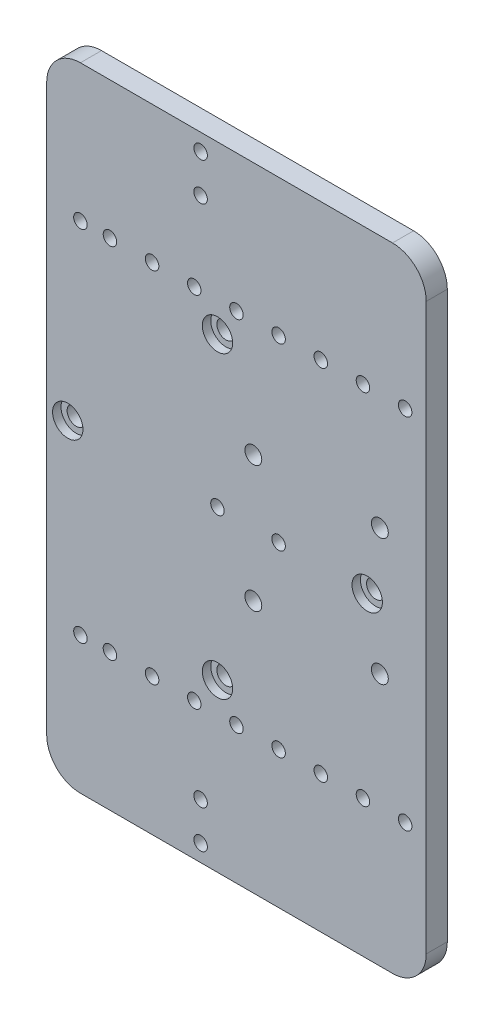
SolidWorks part; units mm, degrees
ref_plane "前视基准面" through (0, 0, 0) normal (0, 0, 1) x (1, 0, 0)
ref_plane "上视基准面" through (0, 0, 0) normal (0, 1, 0) x (1, 0, 0)
ref_plane "右视基准面" through (0, 0, 0) normal (1, 0, 0) x (0, 0, -1)
sketch "草图1" plane through (0, 0, 0) normal (0, 0, 1) x (1, 0, 0)
  line L1 (0, 0) -> (90, 0)
  line L2 (0, 0) -> (0, -150)
  line L3 (0, -150) -> (90, -150)
  line L4 (90, 0) -> (90, -150)
  circle A4 centre (79, -60) radius 2
  circle A5 centre (79, -90) radius 2
  circle A12 centre (49, -60) radius 2
  circle A13 centre (49, -90) radius 2
  circle A14 centre (40.5, -39.5) radius 2.15
  circle A15 centre (40.5, -110.5) radius 2.15
  circle A16 centre (76, -75) radius 2.15
  circle A17 centre (5, -75) radius 2.15
  circle A18 centre (85, -117.5) radius 1.6
  circle A19 centre (75, -117.5) radius 1.6
  circle A20 centre (65, -117.5) radius 1.6
  circle A21 centre (55, -117.5) radius 1.6
  circle A22 centre (45, -117.5) radius 1.6
  circle A23 centre (85, -32.5) radius 1.6
  circle A24 centre (75, -32.5) radius 1.6
  circle A25 centre (65, -32.5) radius 1.6
  circle A26 centre (55, -32.5) radius 1.6
  circle A27 centre (45, -32.5) radius 1.6
  circle A28 centre (35, -117.5) radius 1.6
  circle A29 centre (25, -117.5) radius 1.6
  circle A30 centre (15, -117.5) radius 1.6
  circle A31 centre (35, -32.5) radius 1.6
  circle A32 centre (25, -32.5) radius 1.6
  circle A33 centre (15, -32.5) radius 1.6
  circle A34 centre (8, -117.5) radius 1.6
  circle A35 centre (8, -32.5) radius 1.6
  circle A36 centre (36.5, -4) radius 1.6
  circle A37 centre (36.5, -13) radius 1.6
  circle A38 centre (36.5, -137) radius 1.6
  circle A39 centre (36.5, -146) radius 1.6
  circle A40 centre (55, -75) radius 1.6
  circle A41 centre (40.5, -75) radius 1.6
  dimension "D1" = 150
  dimension "D15" = 2
  dimension "D5" = 30
  dimension "D16" = 2
  dimension "D17" = 2
  dimension "D18" = 39.5
  dimension "D7" = 49
  dimension "D19" = 71
  dimension "D21" = 71
  dimension "D3" = 75
  dimension "D4" = 32.5
  dimension "D6" = 3.2
  dimension "D12" = 5
  dimension "D23" = 7
  dimension "D24" = 4
  dimension "D25" = 36.5
  dimension "D28" = 4
  dimension "D29" = 9
  dimension "D30" = 50
  dimension "D31" = 35.5
  dimension "D2" = 90
  dimension "D8" = 60
  dimension "D9" = 5
  dimension "D10" = 30
  dimension "D11" = 2
  dimension "D13" = 4
  dimension "D14" = 2
  dimension "D20" = 40.5
  dimension "D22" = 5
  dimension "D26" = 2
  dimension "D27" = 2
extrude "凸台-拉伸1" add sketch "草图1" along normal blind 5
fillet "圆角1" radius 8 4 edges at (0, -150, 2.5) (90, -150, 2.5) (90, 0, 2.5) (0, 0, 2.5)
sketch "草图2" plane through (0, 0, 5) normal (0, 0, 1) x (1, 0, 0)
  circle A0 centre (40.5, -39.5) radius 3.6
  circle A1 centre (76, -75) radius 3.6
  circle A2 centre (5, -75) radius 3.6
  circle A3 centre (40.5, -110.5) radius 3.6
  circle A5 centre (40.5, -39.5) radius 2.15 construction
  circle A6 centre (76, -75) radius 2.15 construction
  circle A7 centre (40.5, -110.5) radius 2.15 construction
  circle A8 centre (5, -75) radius 2.15 construction
extrude "切除-拉伸1" cut sketch "草图2" against normal blind 2
sketch "草图4" plane through (0, 0, 0) normal (0, 0, -1) x (-1, 0, 0)
  arc A0 (-42.1996, -35.0361) -> (-80.4639, -73.3004) centre (-40.5, -75) ccw
  arc A3 (-38.8004, -114.9639) -> (-42.1996, -114.9639) centre (-40.5, -110.5) ccw
  arc A4 (-80.4639, -76.6996) -> (-80.4639, -73.3004) centre (-76, -75) ccw
  arc A6 (-0.5361, -73.3004) -> (-0.5361, -76.6996) centre (-5, -75) ccw
  arc A7 (-42.1996, -35.0361) -> (-38.8004, -35.0361) centre (-40.5, -39.5) ccw
  arc A8 (-80.4639, -76.6996) -> (-42.1996, -114.9639) centre (-40.5, -75) ccw
  arc A9 (-38.8004, -114.9639) -> (-0.5361, -76.6996) centre (-40.5, -75) ccw
  arc A10 (-0.5361, -73.3004) -> (-38.8004, -35.0361) centre (-40.5, -75) ccw
  circle A11 centre (-40.5, -75) radius 30
extrude "凸台-拉伸2" add sketch "草图4" along normal blind 4
